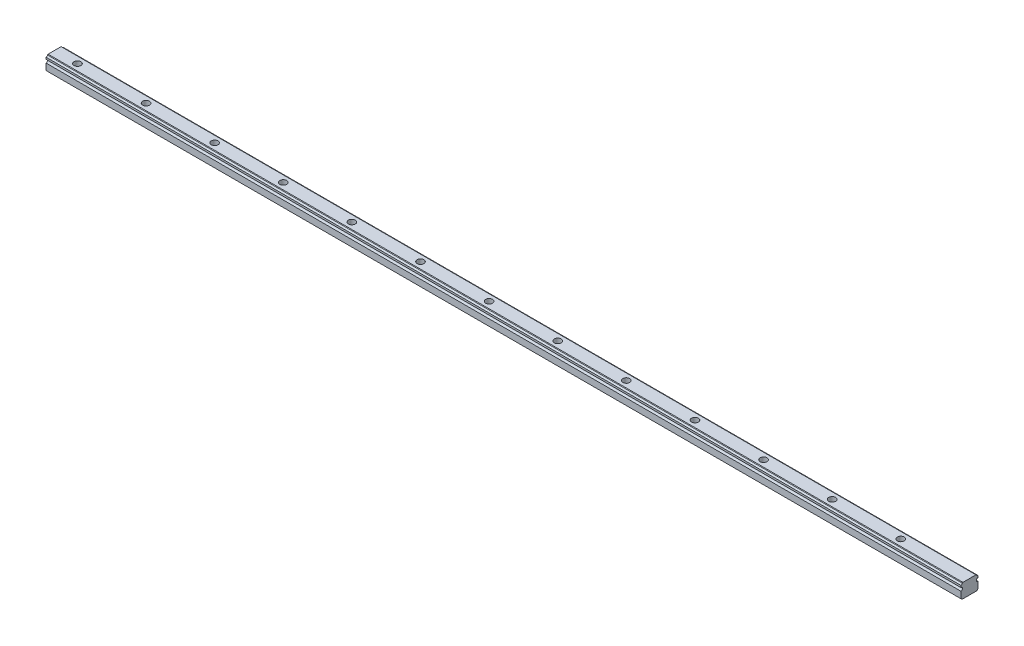
SolidWorks part; units mm, degrees
ref_plane "Front Plane" through (0, 0, 0) normal (0, 0, 1) x (1, 0, 0)
ref_plane "Top Plane" through (0, 0, 0) normal (0, 1, 0) x (1, 0, 0)
ref_plane "Right Plane" through (0, 0, 0) normal (1, 0, 0) x (0, 0, -1)
ref_plane "Plane1" through (-20, 0, 0) normal (1, 0, 0) x (0, 0, -1)
ref_plane "Plane2" through (-10, 0, 0) normal (1, 0, 0) x (0, 0, -1)
ref_plane "Dim. L" through (740, 0, 0) normal (1, 0, 0) x (0, 0, -1)
ref_plane "Plane3" through (730, 0, 0) normal (1, 0, 0) x (0, 0, -1)
sketch "Sketch1" plane through (-20, 0, 0) normal (1, 0, 0) x (0, 0, -1)
  line L0 (-5.6923, 12.5) -> (5.6923, 12.5)
  line L1 (5.6923, 12.5) -> (6.1923, 12)
  line L2 (7.5, 11.1) -> (7.5, 9.5)
  line L3 (7.5, 6.7) -> (7.5, 1)
  line L4 (7.5, 1) -> (6.5, 0)
  line L5 (6.5, 0) -> (-6.5, 0)
  line L6 (0, 12.5) -> (0, 0) construction
  line L7 (-5.6923, 12.5) -> (-6.1923, 12)
  line L8 (-7.5, 11.1) -> (-7.5, 9.5)
  line L9 (-7.5, 6.7) -> (-7.5, 1)
  line L10 (-7.5, 1) -> (-6.5, 0)
  arc A0 (6.1923, 12) -> (7.5, 11.1) centre (7.5, 12.5) ccw
  arc A1 (7.5, 9.5) -> (7.5, 6.7) centre (7.5, 8.1) ccw
  arc A2 (-6.1923, 12) -> (-7.5, 11.1) centre (-7.5, 12.5) cw
  arc A3 (-7.5, 9.5) -> (-7.5, 6.7) centre (-7.5, 8.1) cw
  dimension "FIX_3" = 1.4
  dimension "MSM_3" = 1.4
  dimension "FIX_2" = 45
  dimension "FIX_1" = 45
  dimension "H1" = 12.5
  dimension "MSM_1" = 8.1
  dimension "FIX_4" = 0.5
  dimension "MSM_2" = 1
  dimension "W1" = 15
extrude "Boss-Extrude1" add sketch "Sketch1" along normal blind 800
hole_wizard "Cap Screw1" positions "Sketch3" profile "Sketch2" counterbore size "M3" standard "JIS" end condition through all
sketch "Sketch3" plane through (0, 12.5, 0) normal (0, 1, 0) x (1, 0, 0)
  point P0 (0, 0)
  point P7 (60, 0)
  point P8 (120, 0)
  point P9 (180, 0)
  point P10 (240, 0)
  point P11 (300, 0)
  point P12 (360, 0)
  point P13 (420, 0)
  point P14 (480, 0)
  point P15 (540, 0)
  point P16 (600, 0)
  point P17 (660, 0)
  point P18 (720, 0)
  dimension "F" = 60
  dimension "M" = 13
sketch "Sketch2" plane through (0, 12.5, 0) normal (1, 0, 0) x (0, 0, 1)
  line L0 (0, 0) -> (0, 12.5)
  line L1 (0, 12.5) -> (1.75, 12.5)
  line L3 (1.75, 12.5) -> (1.75, 4.5)
  line L4 (1.75, 4.5) -> (3, 4.5)
  line L5 (3, 4.5) -> (3, 0)
  line L7 (3, 0) -> (0, 0)
  line L11 (0, 0) -> (0, 12.5) construction
  dimension "D1_s" = 3.5
  dimension "Thru Hole Depth" = 12.5
  dimension "D2_s" = 6
  dimension "H_s" = 4.5
other "SurfaceCut1" [suppressed]
other "SurfaceCut2" [suppressed]
scale "缩放比例1" scale about origin uniform scaling yes scale factor 1.7
equation "\"FIX_3@Sketch1\"=\"MSM_3@Sketch1\""
